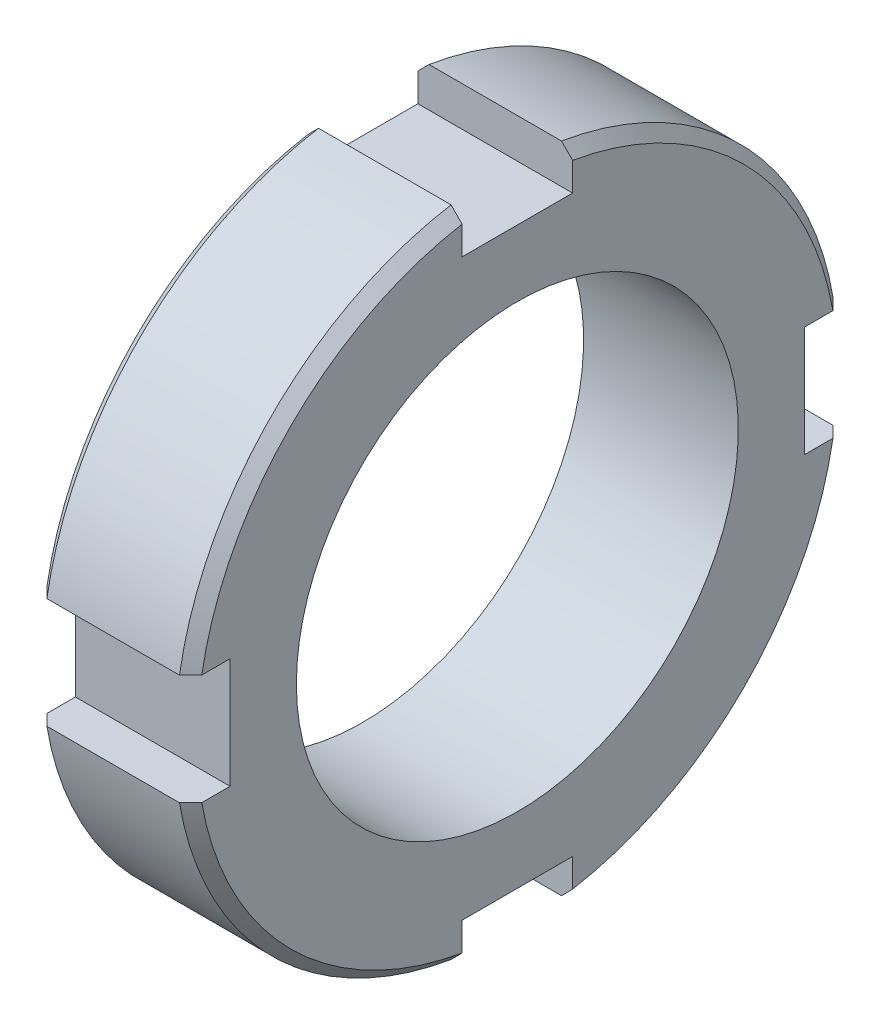
SolidWorks part; units mm, degrees
ref_plane "前视基准面" through (0, 0, 0) normal (0, 0, 1) x (1, 0, 0)
ref_plane "上视基准面" through (0, 0, 0) normal (0, 1, 0) x (1, 0, 0)
ref_plane "右视基准面" through (0, 0, 0) normal (1, 0, 0) x (0, 0, -1)
other "Configuration Table"
sketch "草图1" plane through (0, 0, 0) normal (0, 0, 1) x (1, 0, 0)
  line L0 (-5, 0) -> (12, 0) construction
  line L1 (0, 10) -> (0, 14.5)
  line L2 (0, 14.5) -> (0.5, 15)
  line L3 (0.5, 15) -> (6.5, 15)
  line L4 (6.5, 15) -> (7, 14.5)
  line L5 (7, 14.5) -> (7, 10)
  line L6 (7, 10) -> (0, 10)
revolve "01_RING" add sketch "草图1" angle 360 about L0
ref_plane "P_SLOTS" through (-0.5, 0, 0) normal (1, 0, 0) x (0, 0, -1)
sketch "草图2" plane through (-0.5, 0, 0) normal (1, 0, 0) x (0, 0, -1)
  line L0 (13, -2.5) -> (17, -2.5)
  line L1 (17, -2.5) -> (17, 2.5)
  line L2 (17, 2.5) -> (13, 2.5)
  line L3 (13, 2.5) -> (13, -2.5)
  line L4 (-17, -2.5) -> (-13, -2.5)
  line L5 (-13, -2.5) -> (-13, 2.5)
  line L6 (-13, 2.5) -> (-17, 2.5)
  line L7 (-17, 2.5) -> (-17, -2.5)
  line L8 (-2.5, 13) -> (2.5, 13)
  line L9 (2.5, 13) -> (2.5, 17)
  line L10 (2.5, 17) -> (-2.5, 17)
  line L11 (-2.5, 17) -> (-2.5, 13)
  line L12 (-2.5, -17) -> (2.5, -17)
  line L13 (2.5, -17) -> (2.5, -13)
  line L14 (2.5, -13) -> (-2.5, -13)
  line L15 (-2.5, -13) -> (-2.5, -17)
extrude "02_SLOTS" cut sketch "草图2" along normal blind 8
